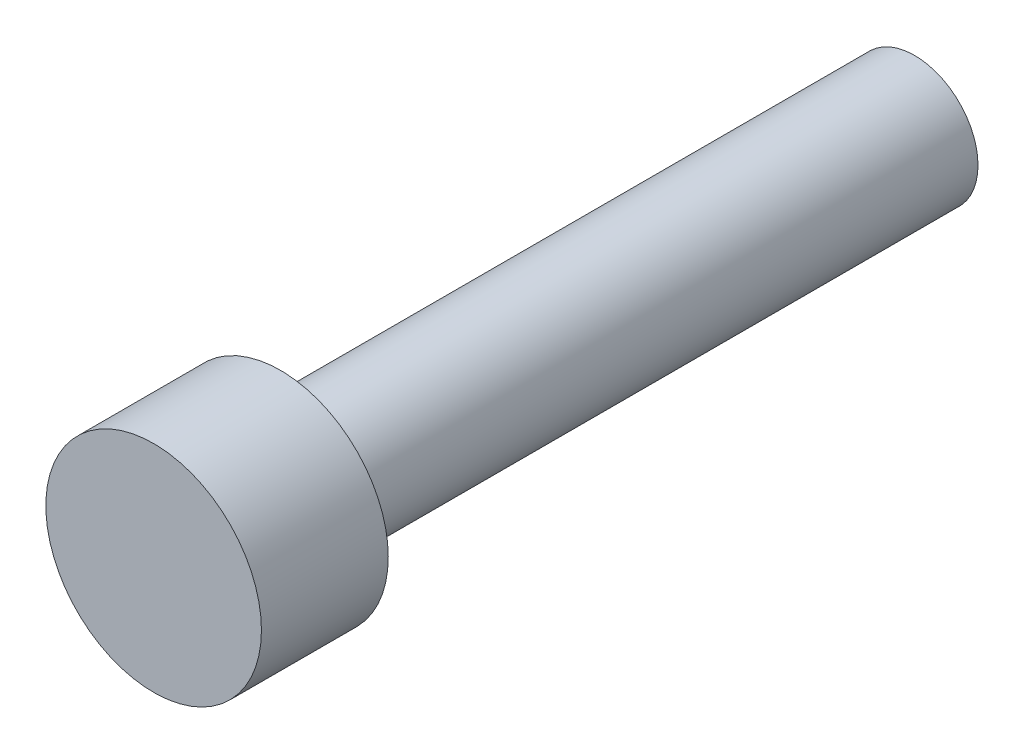
SolidWorks part; units mm, degrees
ref_plane "前视基准面" through (0, 0, 0) normal (0, 0, 1) x (1, 0, 0)
ref_plane "上视基准面" through (0, 0, 0) normal (0, 1, 0) x (1, 0, 0)
ref_plane "右视基准面" through (0, 0, 0) normal (1, 0, 0) x (0, 0, -1)
other "Configuration Table"
sketch "草图1" plane through (0, 0, 0) normal (1, 0, 0) x (0, 0, -1)
  line L0 (-10, 0) -> (30, 0) construction
  line L1 (25, 0) -> (25, 2.5)
  line L2 (25, 2.5) -> (0, 2.5)
  line L3 (0, 2.5) -> (0, 4.25)
  line L4 (0, 4.25) -> (-5, 4.25)
  line L5 (-5, 4.25) -> (-5, 0)
  line L6 (-5, 0) -> (25, 0)
revolve "旋转1" add sketch "草图1" angle 360 about L0
